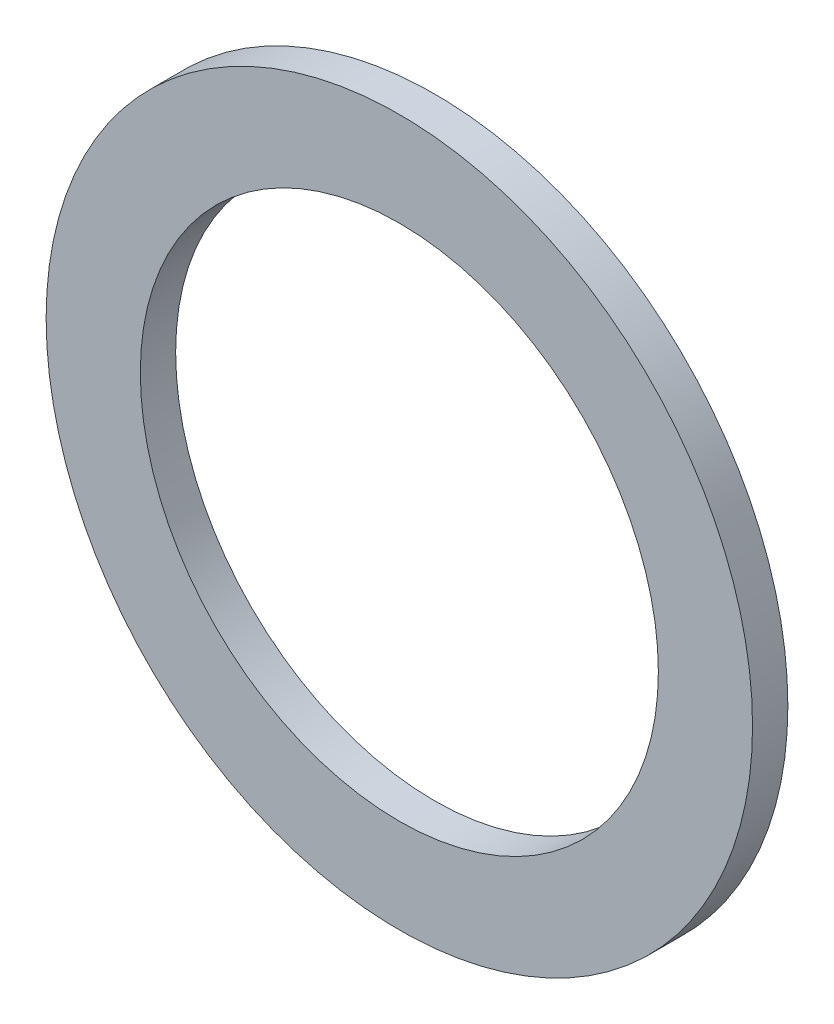
SolidWorks part; units mm, degrees
material "PA Type 6"
ref_plane "Front Plane" through (0, 0, 0) normal (0, 0, 1) x (1, 0, 0)
ref_plane "Top Plane" through (0, 0, 0) normal (0, 1, 0) x (1, 0, 0)
ref_plane "Right Plane" through (0, 0, 0) normal (1, 0, 0) x (0, 0, -1)
sketch "Sketch1" plane through (0, 0, 0) normal (0, 0, 1) x (1, 0, 0)
  circle A0 centre (0, 0) radius 11
  circle A1 centre (0, 0) radius 15
  dimension "D1" = 22
  dimension "D2" = 30
extrude "Boss-Extrude1" add sketch "Sketch1" along normal blind 1.5
